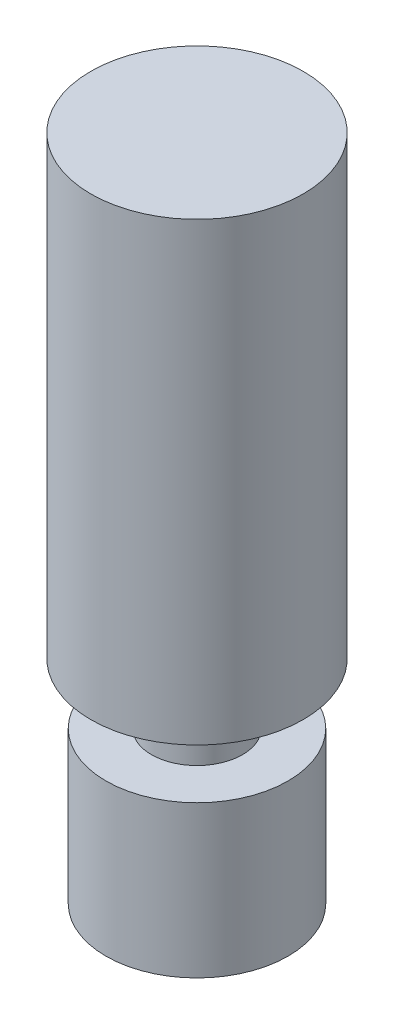
SolidWorks part; units mm, degrees
ref_plane "Front" through (0, 0, 0) normal (0, 0, 1) x (1, 0, 0)
ref_plane "Top" through (0, 0, 0) normal (0, 1, 0) x (1, 0, 0)
ref_plane "Right" through (0, 0, 0) normal (1, 0, 0) x (0, 0, -1)
sketch "Sketch1" plane through (0, 0, 0) normal (0, 0, 1) x (1, 0, 0)
  line L0 (0, 0) -> (0, 22) construction
  line L1 (0, 22) -> (3.5, 22)
  line L2 (3.5, 22) -> (3.5, 7)
  line L3 (3.5, 7) -> (1.5, 7)
  line L4 (1.5, 7) -> (1.5, 5)
  line L5 (1.5, 5) -> (3, 5)
  line L6 (3, 5) -> (3, 0)
  line L7 (3, 0) -> (0, 0)
  line L8 (0, 0) -> (0, 22)
  dimension "D1" = 22
  dimension "D2" = 7
  dimension "D3" = 6
  dimension "D4" = 15
  dimension "D5" = 2
  dimension "D6" = 3
revolve "Revolve1" add sketch "Sketch1" angle 360 about L0
